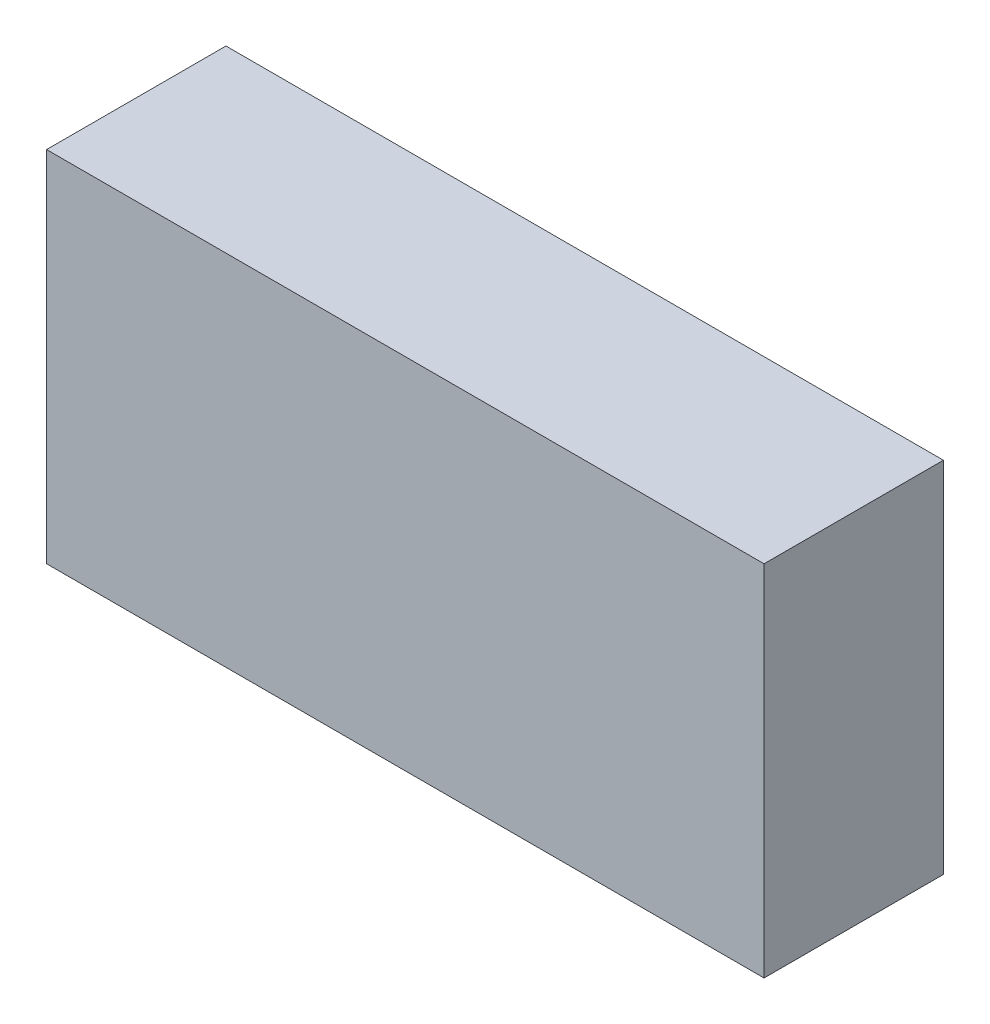
SolidWorks part; units mm, degrees
ref_plane "Front Plane" through (0, 0, 0) normal (0, 0, 1) x (1, 0, 0)
ref_plane "Top Plane" through (0, 0, 0) normal (0, 1, 0) x (1, 0, 0)
ref_plane "Right Plane" through (0, 0, 0) normal (1, 0, 0) x (0, 0, -1)
sketch "RectangleSketch" plane through (0, 0, 0) normal (0, 0, 1) x (1, 0, 0)
  line L1 (0, 0) -> (40, 0)
  line L2 (0, 0) -> (0, 20)
  line L3 (0, 20) -> (40, 20)
  line L4 (40, 0) -> (40, 20)
  dimension "width_mm" = 40
  dimension "height_mm" = 20
extrude "BlindBoss" add sketch "RectangleSketch" against normal blind 10 separate body
